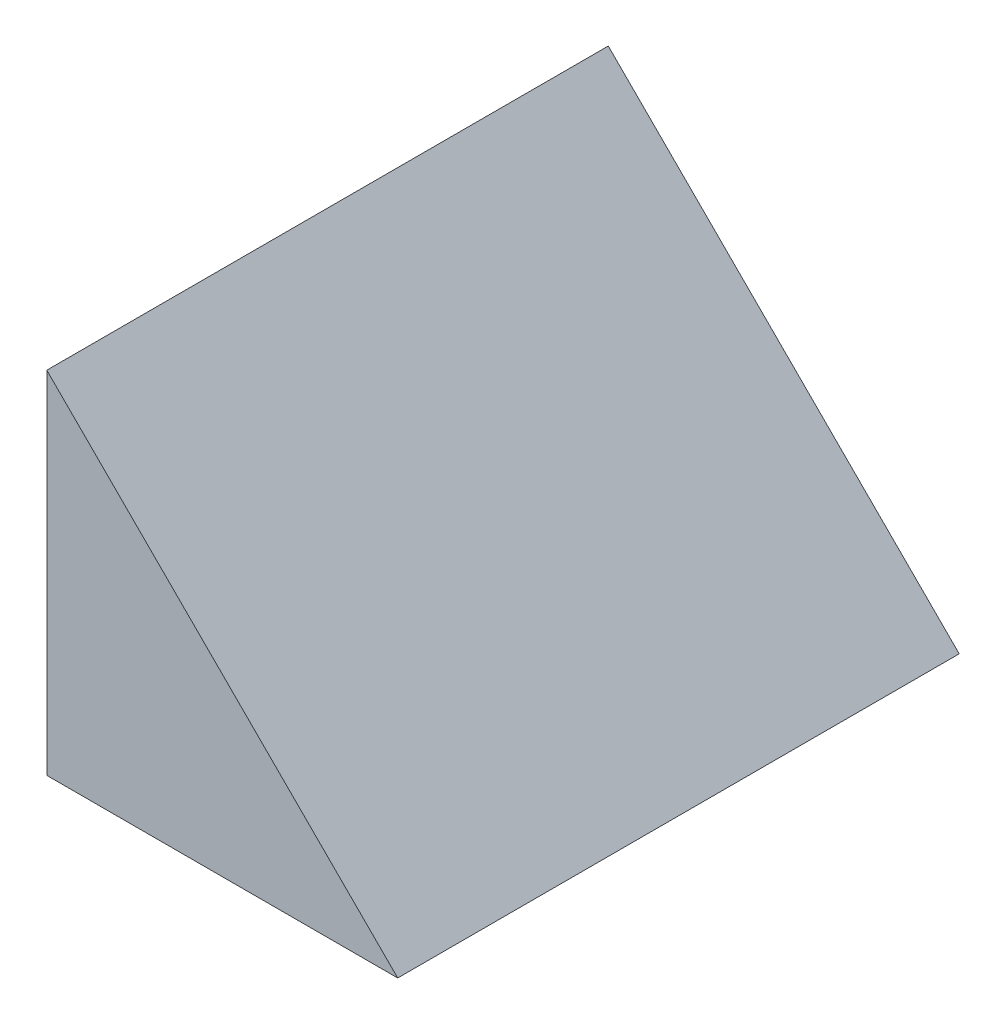
SolidWorks part; units mm, degrees
ref_plane "Front Plane" through (0, 0, 0) normal (0, 0, 1) x (1, 0, 0)
ref_plane "Top Plane" through (0, 0, 0) normal (0, 1, 0) x (1, 0, 0)
ref_plane "Right Plane" through (0, 0, 0) normal (1, 0, 0) x (0, 0, -1)
sketch "Sketch1" plane through (0, 0, 0) normal (0, 0, 1) x (1, 0, 0)
  line L0 (0, 0) -> (0, 0.25)
  line L1 (0, 0) -> (0.25, 0)
  line L5 (0, 0.25) -> (0.25, 0)
  dimension "D1" = 0.25
  dimension "D2" = 0.25
extrude "Boss-Extrude1" add sketch "Sketch1" along normal blind 0.4
equation "\"t\"= 0.25'thickness of the sheets"
equation "\"t_cf\"= 0.115'thickness of single carbon fiber layer"
equation "\"t_kapton\"= 0.025'thickness of single Kapton flex layer"
equation "\"t_fr4\"= 0.1'thickness of FR4 with copper layer"
equation "\"joint_flex\"= 0.1'Width of flextures gap"
equation "\"joint_flex_eff\"= 0.02'Width of flecture after castelation"
equation "\"joint_fold\"= 0.2'Width of folding joints for 90deg fold"
equation "\"gap_tolerance\"= 0.002'Width to have interfecence fit between carbon fiber inserts"
equation "\"assemble_angle\"= 90'Angle of assembly parts"
equation "\"link_lift\"= 0.5'Actuation linkage amplification for the lift motion"
equation "\"link_swing\"= 0.45'Actuation linkage amplification for the swing motion"
equation "\"D1@Boss-Extrude1\"=\"joint_fold\""
equation "\"D1@Sketch1\"=\"t\""
equation "\"D2@Sketch1\"=\"t\""
